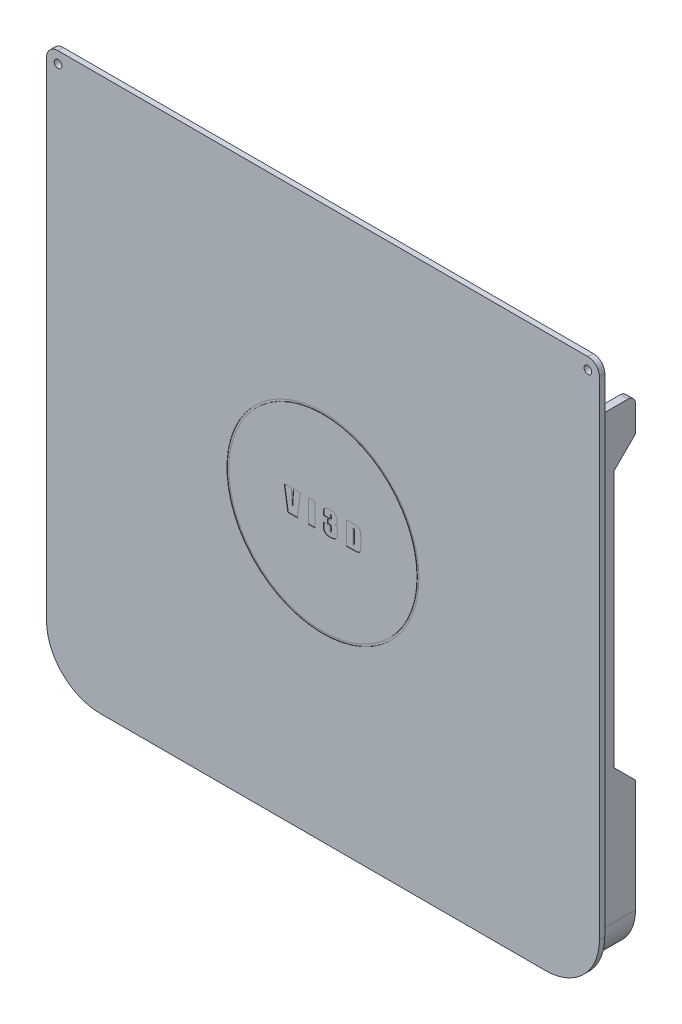
SolidWorks part; units mm, degrees
ref_plane "Front Plane" through (0, 0, 0) normal (0, 0, 1) x (1, 0, 0)
ref_plane "Top Plane" through (0, 0, 0) normal (0, 1, 0) x (1, 0, 0)
ref_plane "Right Plane" through (0, 0, 0) normal (1, 0, 0) x (0, 0, -1)
sketch "Sketch1" plane through (0, 0, 0) normal (0, 0, 1) x (1, 0, 0)
  line L1 (-58, -72) -> (58, -72)
  line L2 (-72, -58) -> (-72, 72)
  line L3 (-72, 72) -> (72, 72)
  line L4 (72, -58) -> (72, 72)
  line L5 (-72, -72) -> (72, 72) construction
  line L6 (-72, 72) -> (72, -72) construction
  arc A0 (58, -72) -> (72, -58) centre (58, -58) ccw
  arc A1 (-58, -72) -> (-72, -58) centre (-58, -58) cw
  point P0 (0, 0)
  dimension "D3" = 14
  dimension "D1" = 144
  dimension "D2" = 144
extrude "Boss-Extrude1" add sketch "Sketch1" along normal blind 1.4
sketch "Sketch2" plane through (0, 0, 0) normal (0, 0, -1) x (-1, 0, 0)
  line L4 (-68, 68) -> (-68, -58)
  line L5 (-58, -68) -> (58, -68)
  line L6 (68, -58) -> (68, 68)
  line L7 (68, 68) -> (-68, 68)
  line L8 (-70, 70) -> (-70, -58)
  line L9 (-58, -70) -> (58, -70)
  line L10 (70, -58) -> (70, 70)
  line L11 (70, 70) -> (-70, 70)
  line L12 (-70, 70) -> (-70, -58)
  line L13 (-58, -70) -> (58, -70)
  line L14 (70, -58) -> (70, 70)
  line L15 (70, 70) -> (-70, 70)
  arc A2 (-68, -58) -> (-58, -68) centre (-58, -58) ccw
  arc A3 (58, -68) -> (68, -58) centre (58, -58) ccw
  arc A4 (-70, -58) -> (-58, -70) centre (-58, -58) ccw
  arc A5 (58, -70) -> (70, -58) centre (58, -58) ccw
  arc A6 (-70, -58) -> (-58, -70) centre (-58, -58) ccw
  arc A7 (58, -70) -> (70, -58) centre (58, -58) ccw
  dimension "D1" = 2
  dimension "D2" = 2
extrude "Boss-Extrude2" add sketch "Sketch2" along normal blind 10
sketch "Sketch3" plane through (70, 0, 0) normal (1, 0, 0) x (0, 0, -1)
  line L0 (10, 49.3958) -> (4.3431, 43.739)
  line L1 (10, 70) -> (10, -58) construction
  line L2 (4.3431, 43.739) -> (4.3431, -23.065)
  line L3 (4.3431, -23.065) -> (10, -28.7218)
  line L4 (10, -28.7218) -> (10, 49.3958)
extrude "Cut-Extrude1" cut sketch "Sketch3" against normal blind 160
fillet "Fillet1" radius 3 4 edges at (-70, 70, -5) (70, 70, -5) (-72, 72, 0.7) (72, 72, 0.7)
sketch "Sketch4" plane through (0, 70, 0) normal (0, 1, 0) x (1, 0, 0)
  line L0 (-67, 10) -> (67, 10) construction
  line L1 (-50, 6) -> (50, 6)
  line L5 (-50, 6) -> (0, 10) construction
  line L6 (0, 10) -> (50, 6) construction
  line L7 (-50, 6) -> (-54, 10)
  line L8 (-54, 10) -> (-50, 10)
  line L9 (-50, 10) -> (50, 10)
  line L11 (50, 6) -> (54, 10)
  line L12 (54, 10) -> (50, 10)
  point P0 (0, 10)
extrude "Cut-Extrude2" cut sketch "Sketch4" against normal blind 160
sketch "Sketch5" plane through (0, 0, 1.4) normal (0, 0, 1) x (1, 0, 0)
  line L9 (69, 72) -> (-69, 72)
  line L10 (-72, 69) -> (-72, -58)
  line L11 (-58, -72) -> (58, -72)
  line L12 (72, -58) -> (72, 69)
  line L13 (69, 72) -> (-69, 72)
  line L14 (-72, 69) -> (-72, -58)
  line L15 (-58, -72) -> (58, -72)
  line L16 (72, -58) -> (72, 69)
  arc A8 (-69, 72) -> (-72, 69) centre (-69, 69) ccw
  arc A9 (-72, -58) -> (-58, -72) centre (-58, -58) ccw
  arc A10 (58, -72) -> (72, -58) centre (58, -58) ccw
  arc A11 (72, 69) -> (69, 72) centre (69, 69) ccw
  arc A12 (-69, 72) -> (-72, 69) centre (-69, 69) ccw
  arc A13 (-72, -58) -> (-58, -72) centre (-58, -58) ccw
  arc A14 (58, -72) -> (72, -58) centre (58, -58) ccw
  arc A15 (72, 69) -> (69, 72) centre (69, 69) ccw
  dimension "D5" = 14
  dimension "D6" = 3
  dimension "D1" = 0
  dimension "D2" = 138
  dimension "D3" = 127
  dimension "D4" = 116
sketch "Sketch6" plane through (0, 0, 0) normal (0, 0, -1) x (-1, 0, 0)
  line L0 (-70, 67) -> (-70, 49.3958) construction
  line L1 (-70, 58.1979) -> (79.1114, 58.1979)
  line L2 (-70, 58.1979) -> (-70, 78.3395)
  line L3 (-70, 78.3395) -> (79.1114, 78.3395)
  line L4 (79.1114, 58.1979) -> (79.1114, 78.3395)
  point P6 (79.1114, 78.5325)
  point P7 (-70, 78.3395)
  point P8 (-70, 58.1979)
extrude "Cut-Extrude3" cut sketch "Sketch6" along normal blind 104
fillet "Fillet2" radius 2 2 edges at (-69, 58.1979, -10) (69, 58.1979, -10)
sketch "Sketch7" plane through (0, 0, 0) normal (0, 0, -1) x (-1, 0, 0)
  circle A0 centre (-69, 69) radius 1
  circle A1 centre (69, 69) radius 1
extrude "Cut-Extrude4" cut sketch "Sketch7" against normal blind 104
sketch "Sketch8" plane through (0, 0, 1.4) normal (0, 0, 1) x (1, 0, 0)
  line L0 (-8, 0) -> (8, 0) construction
  circle A0 centre (0, 0) radius 25
  circle A1 centre (0, 0) radius 24.5
  text T0 "<b>VI3D</b>" font "Century Gothic" height 5
  dimension "D1" = 8
  dimension "D2" = 8
extrude "Cut-Extrude5" cut sketch "Sketch8" against normal blind 0.1 contours A0 A1
sketch "Sketch9" plane through (0, 0, 1.4) normal (0, 0, 1) x (1, 0, 0)
  line L1 (-10, -2.1934) -> (10, -2.1934) construction
  text T0 "<b>VI3D</b>" font "Impact" height 6
extrude "Cut-Extrude6" cut sketch "Sketch9" against normal blind 0.1
